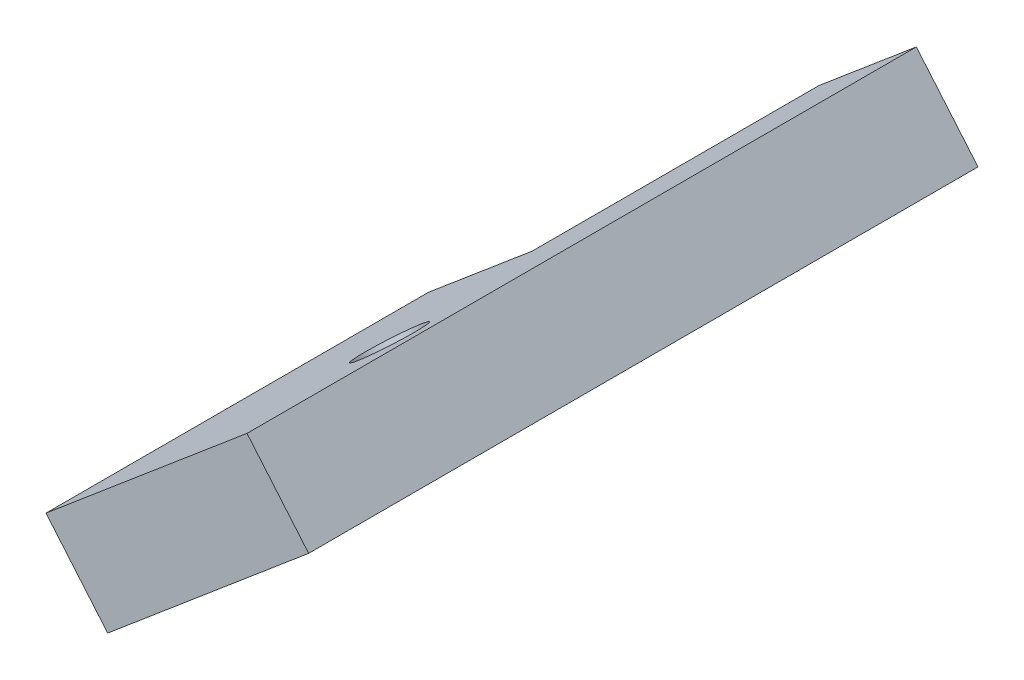
SolidWorks part; units mm, degrees
ref_plane "Front Plane" through (0, 0, 0) normal (0, 0, 1) x (1, 0, 0)
ref_plane "Top Plane" through (0, 0, 0) normal (0, 1, 0) x (1, 0, 0)
ref_plane "Right Plane" through (0, 0, 0) normal (1, 0, 0) x (0, 0, -1)
sketch "Sketch4" plane through (454.1451, -538.3327, 0) normal (0.6448, -0.7643, 0) x (0.7643, 0.6448, 0)
  line L1 (554.952, 0) -> (554.952, 12)
  line L2 (554.952, 12) -> (546.702, 12)
  line L3 (546.702, 12) -> (546.702, 0)
  line L4 (546.702, 0) -> (550.952, 0)
  line L5 (550.952, 0) -> (550.952, -9)
  line L6 (550.952, -9) -> (554.952, -9)
  line L7 (554.952, -9) -> (550.952, -9) construction
  line L8 (554.952, -9) -> (554.952, 0)
  line L9 (554.952, -9) -> (554.952, 0) construction
  circle A0 centre (552.952, 6) radius 1
  dimension "D1" = 2
  dimension "D2" = 2
  dimension "D3" = 6
  dimension "D4" = 6
extrude "Boss-Extrude1" add sketch "Sketch4" along normal up to surface (3 mm away)
